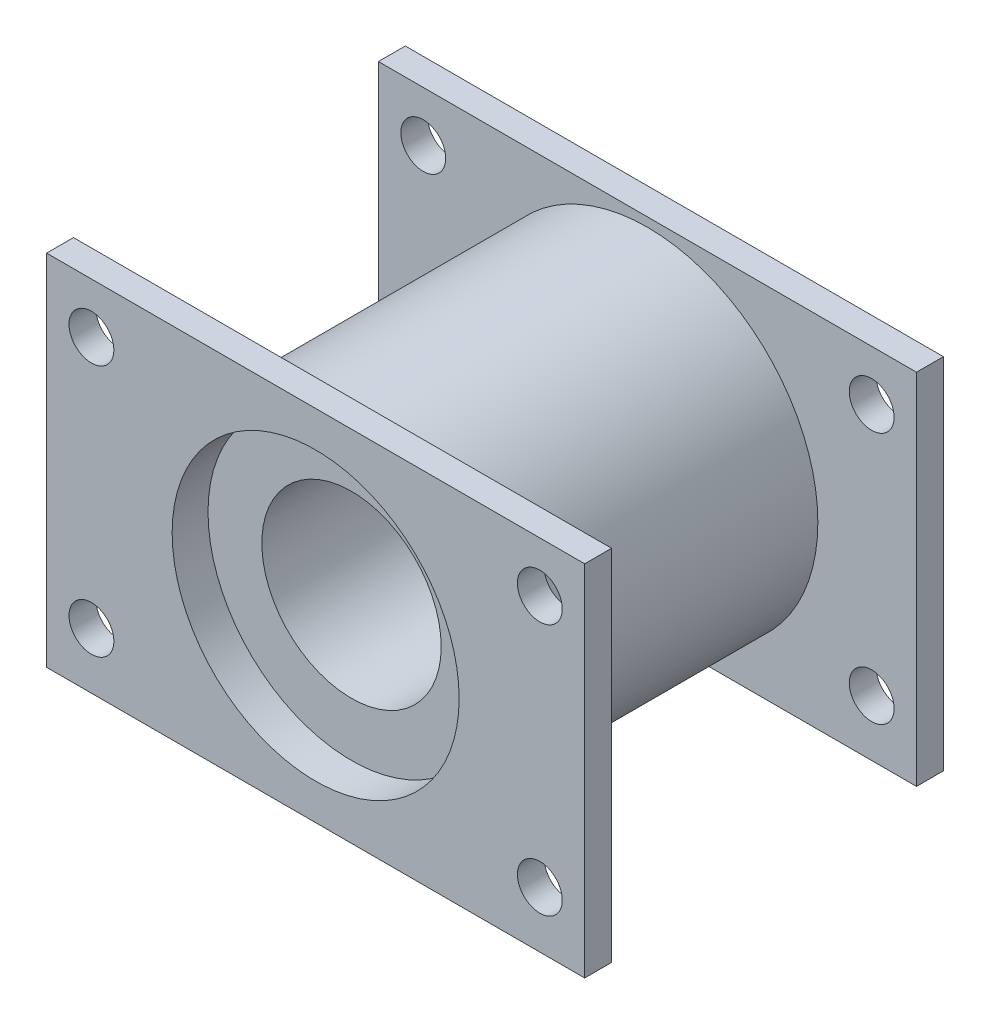
SolidWorks part; units mm, degrees
ref_plane "Front Plane" through (0, 0, 0) normal (0, 0, 1) x (1, 0, 0)
ref_plane "Top Plane" through (0, 0, 0) normal (0, 1, 0) x (1, 0, 0)
ref_plane "Right Plane" through (0, 0, 0) normal (1, 0, 0) x (0, 0, -1)
sketch "Sketch1" plane through (0, 0, 0) normal (0, 0, 1) x (1, 0, 0)
  circle A0 centre (0, 0) radius 16
  circle A1 centre (0, 0) radius 19
  dimension "D1" = 32
  dimension "D2" = 38
extrude "Boss-Extrude1" add sketch "Sketch1" along normal blind 40
sketch "Sketch2" plane through (0, 0, 0) normal (0, 0, -1) x (-1, 0, 0)
  line L1 (-30, 20) -> (30, 20)
  line L2 (-30, 20) -> (-30, -20)
  line L3 (-30, -20) -> (30, -20)
  line L4 (30, 20) -> (30, -20)
  line L5 (-30, 20) -> (30, -20) construction
  line L6 (-30, -20) -> (30, 20) construction
  circle A0 centre (0, 0) radius 19
  point P0 (0, 0)
  dimension "D1" = 60
  dimension "D2" = 40
extrude "Boss-Extrude2" add sketch "Sketch2" against normal blind 3
ref_plane "Plane1" through (0, 0, 20) normal (0, 0, 1) x (1, 0, 0)
mirror "Mirror1" about plane through (0, 0, 20) normal (0, 0, 1) of "Boss-Extrude2"
sketch "Sketch4" plane through (0, 0, 0) normal (0, 0, -1) x (-1, 0, 0)
  line L0 (-36.5313, 0) -> (37.6952, 0) construction
  line L1 (0, 23.4382) -> (0, -25.2487) construction
  circle A0 centre (-25, 14.3862) radius 2.5
  circle A1 centre (25, 14.3862) radius 2.5
  circle A2 centre (-25, -13.7397) radius 2.5
  circle A3 centre (25, -13.7397) radius 2.5
  dimension "D1" = 5
  dimension "D2" = 5
  dimension "D3" = 5
  dimension "D4" = 5
  dimension "D5" = 25
  dimension "D6" = 25
  dimension "D7" = 25
  dimension "D8" = 25
extrude "Cut-Extrude1" cut sketch "Sketch4" against normal through all
sketch "Sketch6" plane through (0, 0, 20) normal (0, 0, 1) x (1, 0, 0)
  circle A0 centre (0, 0) radius 16
  circle A1 centre (0, 0) radius 10
  dimension "D1" = 20
extrude "Boss-Extrude3" add sketch "Sketch6" along normal blind 16 and the other way blind 16
